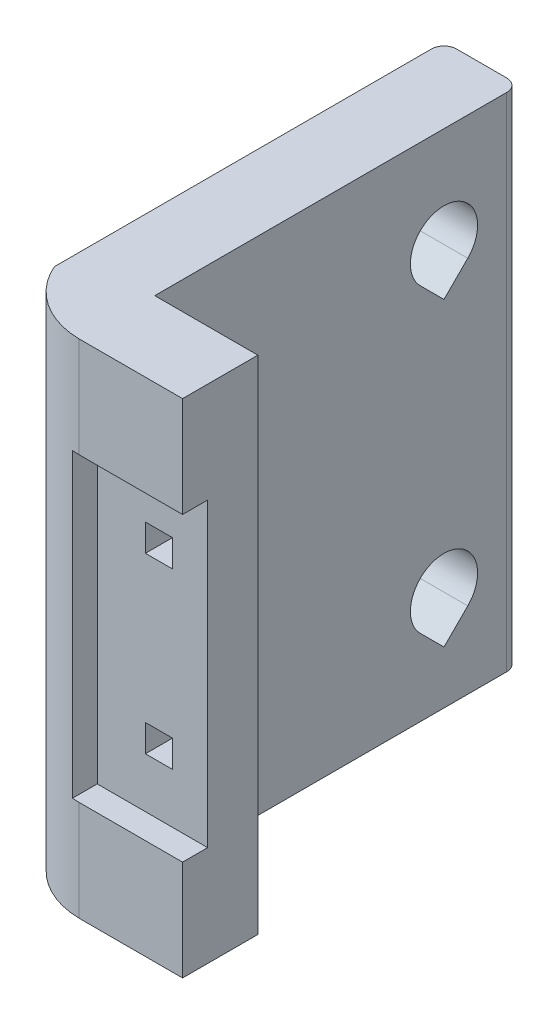
SolidWorks part; units mm, degrees
ref_plane "Front Plane" through (0, 0, 0) normal (1, 0, 0) x (0, 1, 0)
ref_plane "Top Plane" through (0, 0, 0) normal (0, 0, 1) x (0, 1, 0)
ref_plane "Right Plane" through (0, 0, 0) normal (0, 1, 0) x (-1, 0, 0)
sketch "Sketch1" plane through (0, 0, 0) normal (0, 1, 0) x (-1, 0, 0)
  line L1 (-16.5394, 20.3051) -> (-16.4627, 20.3051)
  line L2 (-16.5394, 5.3051) -> (-16.5394, -67.3449)
  line L3 (-16.5394, -67.3449) -> (-1.5394, -67.3449)
  line L4 (-1.5394, 10.3051) -> (-1.5394, -67.3449)
  line L7 (-16.5394, 20.3051) -> (-37.0851, 20.3051)
  line L9 (-16.5394, 5.3051) -> (-37.0851, 5.3051)
  line L10 (-37.0851, 20.3051) -> (-37.0851, 5.3051)
  arc A1 (-16.4627, 20.3051) -> (-1.5394, 10.3051) centre (-16.7339, 3.7651) cw
  point P0 (0, 0)
  dimension "D1" = 77.65
  dimension "D2" = 15
  dimension "D3" = 72.65
  dimension "D4" = 15
extrude "Boss-Extrude1" add sketch "Sketch1" along normal blind 100
sketch "Sketch2" plane through (1.5394, 0, 0) normal (-1, 0, 0) x (0, -1, 0)
  line L0 (-50, 10.3051) -> (-50, -67.3449) construction
  line L1 (-100, 10.3051) -> (0, 10.3051) construction
  line L2 (-100, -67.3449) -> (0, -67.3449) construction
  line L3 (-100.4701, -28.5199) -> (0, -28.5199) construction
  line L4 (0, -67.3449) -> (0, 10.3051) construction
  line L5 (-100, -67.3449) -> (-100, 10.3051) construction
  line L6 (-73.3, -52.3449) -> (-13.3, -52.3449) construction
  line L7 (-75.2624, -47.6073) -> (-70.5248, -52.3449)
  line L8 (-70.5248, -52.3449) -> (-75.2624, -57.0825)
  line L9 (-10.5248, -52.3449) -> (-15.2624, -47.6073)
  line L10 (-10.5248, -52.3449) -> (-15.2624, -57.0825)
  line L11 (-10.5248, -52.3449) -> (0, -52.3449) construction
  arc A0 (-75.2624, -47.6073) -> (-75.2624, -57.0825) centre (-80, -52.3449) ccw
  arc A1 (-15.2624, -57.0825) -> (-15.2624, -47.6073) centre (-20, -52.3449) cw
  dimension "D1" = 20
  dimension "D2" = 15
  dimension "D3" = 13.4
  dimension "D4" = 45
  dimension "D5" = 45
  dimension "D6" = 45
extrude "Cut-Extrude1" cut sketch "Sketch2" against normal through all
sketch "Sketch3" plane through (0, 0, 20.3051) normal (0, 0, 1) x (1, 0, 0)
  line L0 (37.0851, 20) -> (37.0851, 42.5) construction
  line L1 (37.0851, 100) -> (37.0851, 0) construction
  line L2 (24.6851, 35.4) -> (30.0851, 35.4)
  line L3 (24.6851, 35.4) -> (24.6851, 30)
  line L4 (24.6851, 30) -> (30.0851, 30)
  line L5 (30.0851, 35.4) -> (30.0851, 30)
  line L10 (37.0851, 0) -> (37.0851, 20) construction
  line L11 (37.0851, 42.5) -> (37.0851, 57.5) construction
  line L12 (37.0851, 57.5) -> (37.0851, 80) construction
  line L13 (37.0851, 80) -> (37.0851, 100) construction
  line L14 (37.0851, 50) -> (16.4627, 50) construction
  line L15 (16.4627, 100) -> (16.4627, 0) construction
  line L16 (30.0851, 64.6) -> (30.0851, 70)
  line L17 (24.6851, 70) -> (30.0851, 70)
  line L18 (24.6851, 64.6) -> (24.6851, 70)
  line L19 (24.6851, 64.6) -> (30.0851, 64.6)
  dimension "D1" = 5.4
  dimension "D2" = 5.4
  dimension "D3" = 7
  dimension "D4" = 22.5
  dimension "D5" = 14.6
extrude "Cut-Extrude2" cut sketch "Sketch3" against normal through all
sketch "Sketch4" plane through (0, 0, 20.3051) normal (0, 0, 1) x (1, 0, 0)
  line L0 (37.0851, 100) -> (37.0851, 0) construction
  line L1 (37.0851, 80) -> (15.0851, 80)
  line L2 (37.0851, 80) -> (37.0851, 20)
  line L3 (37.0851, 20) -> (15.0851, 20)
  line L4 (15.0851, 80) -> (15.0851, 20)
  line L5 (16.4627, 100) -> (37.0851, 100) construction
  dimension "D1" = 60
  dimension "D2" = 22
  dimension "D3" = 20
extrude "Cut-Extrude3" cut sketch "Sketch4" against normal blind 5
fillet "Fillet1" radius 2.5 2 edges at (1.5394, 50, -67.3449) (16.5394, 50, -67.3449)
